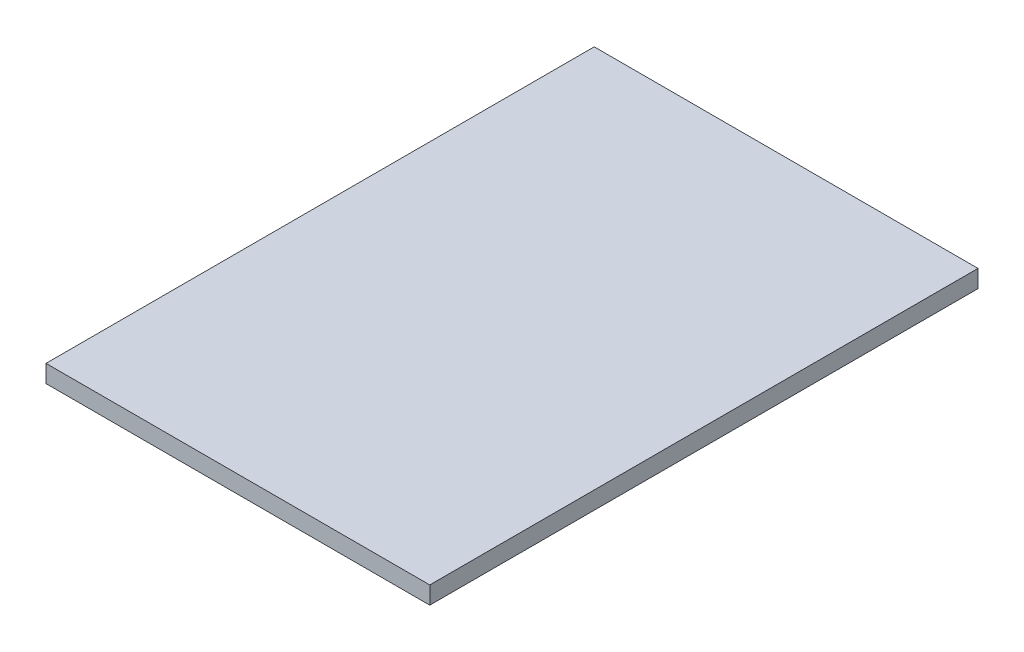
SolidWorks part; units mm, degrees
ref_plane "Front Plane" through (0, 0, 0) normal (0, 0, 1) x (1, 0, 0)
ref_plane "Top Plane" through (0, 0, 0) normal (0, 1, 0) x (1, 0, 0)
ref_plane "Right Plane" through (0, 0, 0) normal (1, 0, 0) x (0, 0, -1)
sketch "Sketch1" plane through (0, 0, 0) normal (0, 1, 0) x (1, 0, 0)
  line L1 (-17.5, 25) -> (17.5, 25)
  line L2 (-17.5, 25) -> (-17.5, -25)
  line L3 (-17.5, -25) -> (17.5, -25)
  line L4 (17.5, 25) -> (17.5, -25)
  line L5 (-17.5, 25) -> (17.5, -25) construction
  line L6 (-17.5, -25) -> (17.5, 25) construction
  point P1 (0, 0)
  dimension "D1" = 35
  dimension "D2" = 50
extrude "Boss-Extrude1" add sketch "Sketch1" along normal blind 1.6
